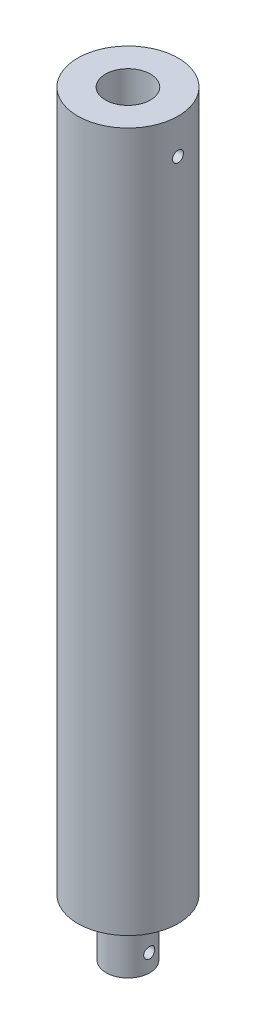
SolidWorks part; units mm, degrees
ref_plane "Front Plane" through (0, 0, 0) normal (0, 0, 1) x (1, 0, 0)
ref_plane "Top Plane" through (0, 0, 0) normal (0, 1, 0) x (1, 0, 0)
ref_plane "Right Plane" through (0, 0, 0) normal (1, 0, 0) x (0, 0, -1)
sketch "Sketch1" plane through (0, 0, 0) normal (0, 1, 0) x (1, 0, 0)
  circle A0 centre (0, 0) radius 6.35
  dimension "D2" = 12.7
extrude "Boss-Extrude1" add sketch "Sketch1" along normal blind 19.05
sketch "Sketch2" plane through (0, 0, 0) normal (1, 0, 0) x (0, 0, -1)
  line L0 (0, 19.05) -> (0, 0) construction
  line L2 (-6.35, 0) -> (6.35, 0) construction
  circle A0 centre (0, 5.08) radius 1.5875
  dimension "D1" = 3.175
  dimension "D2" = 5.08
extrude "Cut-Extrude1" cut sketch "Sketch2" against normal mid plane 50.8
ref_plane "Plane1" through (0, 16.51, 0) normal (0, 1, 0) x (1, 0, 0)
sketch "Sketch4" plane through (0, 16.51, 0) normal (0, 1, 0) x (1, 0, 0)
  circle A0 centre (0, 0) radius 14.605
  circle A1 centre (0, 0) radius 6.35
  circle A2 centre (0, 0) radius 6.35
  dimension "D2" = 29.21
  dimension "D1" = 0
extrude "Boss-Extrude3" add sketch "Sketch4" along normal blind 203.2 separate body
sketch "Sketch5" plane through (0, 0, 0) normal (1, 0, 0) x (0, 0, -1)
  line L0 (0, 219.71) -> (0, 189.4265) construction
  line L1 (6.35, 219.71) -> (-6.35, 219.71) construction
  line L2 (14.605, 219.71) -> (-14.605, 219.71) construction
  circle A0 centre (0, 209.55) radius 1.5875
  dimension "D1" = 3.175
  dimension "D2" = 10.16
extrude "Cut-Extrude2" cut sketch "Sketch5" against normal mid plane 127
sketch "Sketch6" plane through (0, 219.71, 0) normal (0, 1, 0) x (1, 0, 0)
  circle A0 centre (0, 0) radius 6.5405
  dimension "D1" = 13.081
extrude "Cut-Extrude3" cut sketch "Sketch6" against normal mid plane 25.4
